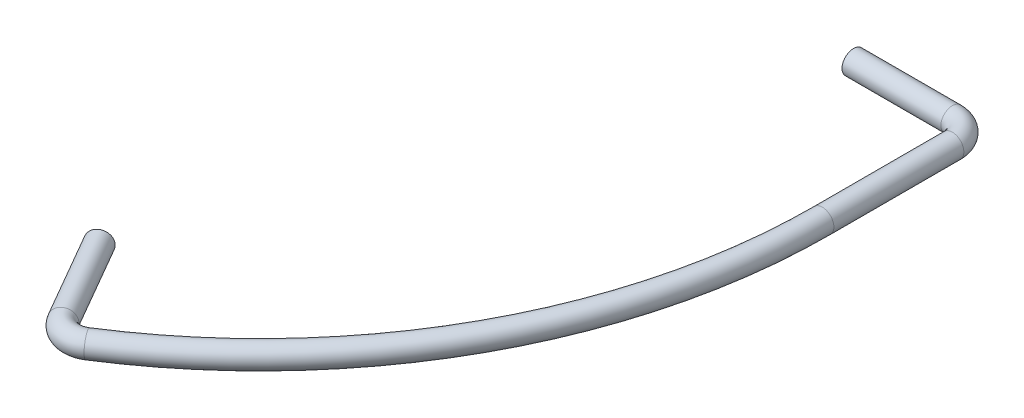
SolidWorks part; units mm, degrees
ref_plane "Front Plane" through (0, 0, 0) normal (0, 0, 1) x (1, 0, 0)
ref_plane "Top Plane" through (0, 0, 0) normal (0, 1, 0) x (1, 0, 0)
ref_plane "Right Plane" through (0, 0, 0) normal (1, 0, 0) x (0, 0, -1)
sketch "Overhead Sketch" plane through (0, 0, 0) normal (0, 1, 0) x (1, 0, 0)
  line L0 (675, 500) -> (675, 0) construction
  line L1 (0, 675) -> (0, -675) construction
  line L2 (0, 0) -> (367.5, -636.5287) construction
  line L3 (0, 0) -> (735, 0) construction
  line L4 (735, 0) -> (735, 170)
  line L5 (705, 200) -> (575.6386, 200)
  line L6 (352.1807, -609.9949) -> (287.5, -497.9646)
  circle A0 centre (0, 0) radius 675 construction
  arc A1 (394.2534, -620.3138) -> (735, 0) centre (0, 0) ccw
  arc A2 (352.1807, -609.9949) -> (394.2534, -620.3138) centre (378.1615, -594.9949) ccw
  arc A3 (735, 170) -> (705, 200) centre (705, 170) ccw
  point P17 (735, 200)
  dimension "D1" = 1350
  dimension "D3" = 60
  dimension "D6" = 160
  dimension "D7" = 30
  dimension "D2" = 500
  dimension "D4" = 30
  dimension "D5" = 200
ref_plane "Cross Section Plane" through (575.6386, 0, 0) normal (-1, 0, 0) x (0, 0, 1)
sketch "Cross Section Sketch" plane through (575.6386, 0, 0) normal (-1, 0, 0) x (0, 0, 1)
  circle A0 centre (-200, 0) radius 15
  dimension "D1" = 30
sweep "Bar Sweep" add profiles "Cross Section Sketch" path "Overhead Sketch"
